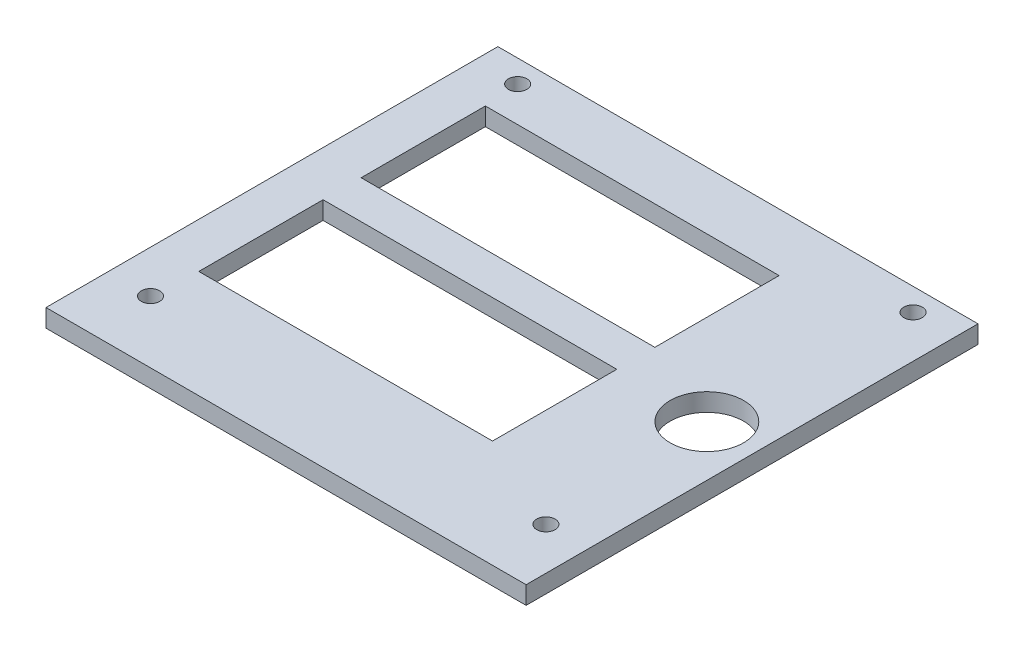
SolidWorks part; units mm, degrees
ref_plane "Front Plane" through (0, 0, 0) normal (0, 0, 1) x (1, 0, 0)
ref_plane "Top Plane" through (0, 0, 0) normal (0, 1, 0) x (1, 0, 0)
ref_plane "Right Plane" through (0, 0, 0) normal (1, 0, 0) x (0, 0, -1)
sketch "Sketch1" plane through (0, 0, 0) normal (0, 1, 0) x (1, 0, 0)
  line L0 (7.5, -4) -> (77.5, -4) construction
  line L1 (0, 0) -> (85, 0)
  line L2 (0, 0) -> (0, -80)
  line L3 (0, -80) -> (85, -80)
  line L4 (85, 0) -> (85, -80)
  line L5 (8, -38.95) -> (60, -38.95)
  line L6 (8, -38.95) -> (8, -60.95)
  line L7 (8, -60.95) -> (60, -60.95)
  line L8 (60, -38.95) -> (60, -60.95)
  line L9 (77.5, -4) -> (77.5, -69) construction
  line L10 (77.5, -69) -> (7.5, -69) construction
  line L11 (7.5, -4) -> (7.5, -69) construction
  line L12 (8, -10.21) -> (60, -10.21)
  line L13 (8, -10.21) -> (8, -32.21)
  line L14 (8, -32.21) -> (60, -32.21)
  line L15 (60, -10.21) -> (60, -32.21)
  circle A2 centre (7.5, -4) radius 1.632
  circle A3 centre (7.5, -69) radius 1.6319
  circle A4 centre (77.5, -69) radius 1.632
  circle A5 centre (77.5, -4) radius 1.632
  circle A6 centre (76, -39) radius 6.5
  dimension "D9" = 3.2639
  dimension "D2" = 13
  dimension "D5" = 80
  dimension "D6" = 85
  dimension "D7" = 52
  dimension "D8" = 22
  dimension "D10" = 6.74
  dimension "D11" = 19.05
  dimension "D12" = 8
  dimension "D13" = 65
  dimension "D14" = 70
  dimension "D15" = 7.5
  dimension "D16" = 8
  dimension "D3" = 9
  dimension "D4" = 39
extrude "Boss-Extrude1" add sketch "Sketch1" along normal blind 3.175
equation "\"D15@Sketch1\"=(\"D6@Sketch1\"-\"D14@Sketch1\")/2"
